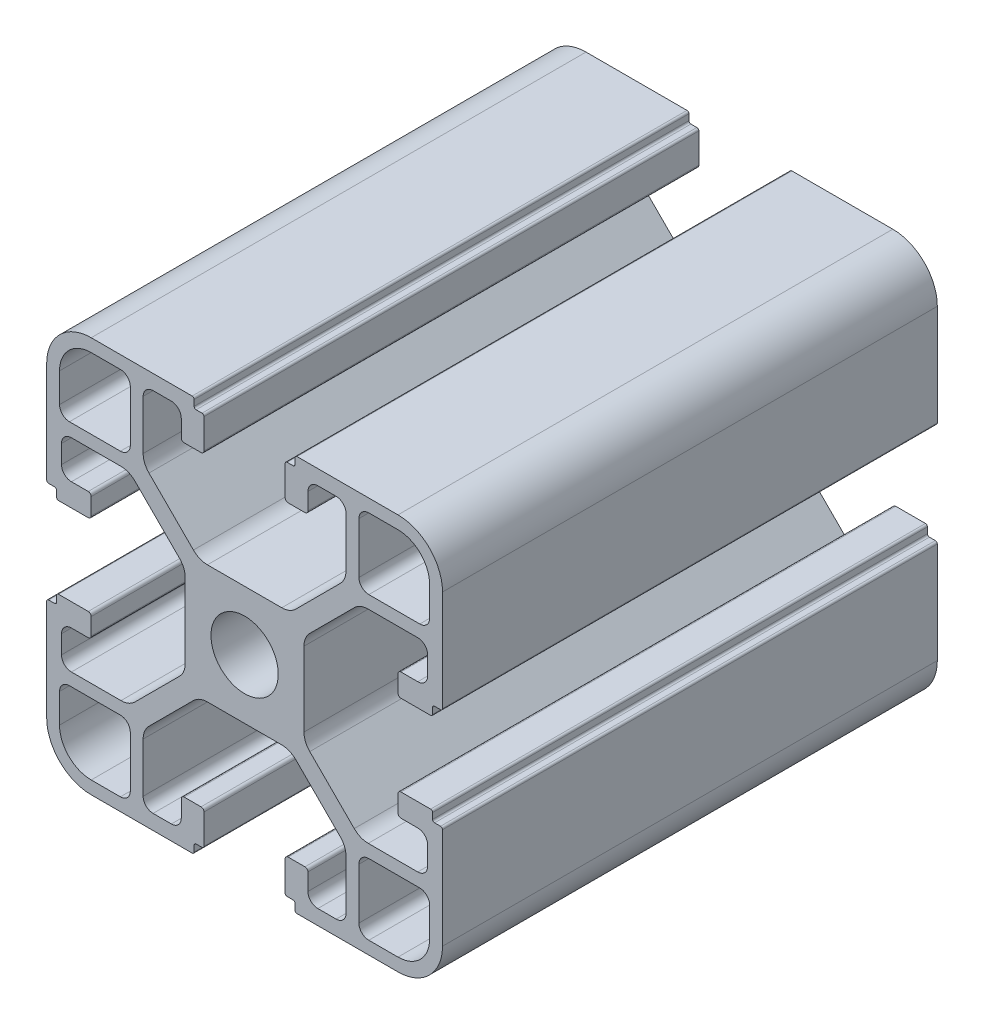
SolidWorks part; units mm, degrees
material "6063-T5"
ref_plane "Front Plane" through (0, 0, 0) normal (0, 0, 1) x (1, 0, 0)
ref_plane "Top Plane" through (0, 0, 0) normal (0, 1, 0) x (1, 0, 0)
ref_plane "Right Plane" through (0, 0, 0) normal (1, 0, 0) x (0, 0, -1)
sketch "Sketch2" plane through (0, 0, 0) normal (0, 0, 1) x (1, 0, 0)
  line L0 (4.5, 0) -> (14.7, 0)
  line L1 (40, 4.5) -> (40, 14.7)
  line L2 (35.5, 40) -> (25.3, 40)
  line L3 (0, 35.5) -> (0, 25.3)
  line L4 (15.9, 1.2) -> (15.9, 4.2)
  line L5 (24.1, 1.2) -> (24.1, 4.2)
  line L6 (38.8, 24.1) -> (35.8, 24.1)
  line L7 (35.5, 24.4) -> (35.5, 26.1)
  line L8 (14, 23.7574) -> (14, 16.2426)
  line L9 (16.2426, 14) -> (23.7574, 14)
  line L10 (26, 16.2426) -> (26, 23.7574)
  line L11 (13.4142, 14.8284) -> (8.9216, 10.3358)
  line L12 (23.7574, 26) -> (16.2426, 26)
  line L13 (4.5, 24.4) -> (4.5, 26.1)
  line L14 (1.2, 24.1) -> (4.2, 24.1)
  line L15 (15.9, 38.8) -> (15.9, 35.8)
  line L16 (14.8284, 26.5858) -> (10.3358, 31.0784)
  line L17 (13.4142, 25.1716) -> (8.9216, 29.6642)
  line L18 (14.8284, 13.4142) -> (10.3358, 8.9216)
  line L19 (25.1716, 13.4142) -> (29.6642, 8.9216)
  line L20 (26.5858, 14.8284) -> (31.0784, 10.3358)
  line L21 (26.5858, 25.1716) -> (31.0784, 29.6642)
  line L22 (25.1716, 26.5858) -> (29.6642, 31.0784)
  line L23 (24.1, 38.8) -> (24.1, 35.8)
  line L24 (14.7, 40) -> (4.5, 40)
  line L25 (25.3, 0) -> (35.5, 0)
  line L26 (38.8, 15.9) -> (35.8, 15.9)
  line L27 (40, 25.3) -> (40, 35.5)
  line L28 (1.2, 15.9) -> (4.2, 15.9)
  line L29 (0, 14.7) -> (0, 4.5)
  line L30 (4.5, 15.6) -> (4.5, 13.9)
  line L31 (35.5, 15.6) -> (35.5, 13.9)
  line L32 (15.6, 35.5) -> (13.9, 35.5)
  line L33 (24.4, 35.5) -> (26.1, 35.5)
  line L34 (15.6, 4.5) -> (13.9, 4.5)
  line L35 (24.4, 4.5) -> (26.1, 4.5)
  line L36 (12.6, 38.5) -> (10.75, 38.5)
  line L37 (1.5, 12.6) -> (1.5, 10.75)
  line L38 (27.4, 1.5) -> (29.25, 1.5)
  line L39 (38.5, 27.4) -> (38.5, 29.25)
  line L40 (38.5, 10.75) -> (38.5, 12.6)
  line L41 (29.25, 38.5) -> (27.4, 38.5)
  line L42 (1.5, 29.25) -> (1.5, 27.4)
  line L43 (10.75, 1.5) -> (12.6, 1.5)
  line L44 (35.8, 26.4) -> (37.5, 26.4)
  line L45 (35.8, 13.6) -> (37.5, 13.6)
  line L46 (4.2, 26.4) -> (2.5, 26.4)
  line L47 (13.6, 35.8) -> (13.6, 37.5)
  line L48 (26.4, 35.8) -> (26.4, 37.5)
  line L49 (4.2, 13.6) -> (2.5, 13.6)
  line L50 (13.6, 4.2) -> (13.6, 2.5)
  line L51 (26.4, 4.2) -> (26.4, 2.5)
  line L52 (9.75, 7.5074) -> (9.75, 2.5)
  line L53 (30.25, 7.5074) -> (30.25, 2.5)
  line L54 (9.75, 37.5) -> (9.75, 32.4926)
  line L55 (30.25, 37.5) -> (30.25, 32.4926)
  line L56 (32.4926, 30.25) -> (37.5, 30.25)
  line L57 (37.5, 9.75) -> (32.4926, 9.75)
  line L58 (2.5, 30.25) -> (7.5074, 30.25)
  line L59 (2.5, 9.75) -> (7.5074, 9.75)
  line L60 (31.55, 37.7) -> (31.55, 32.55)
  line L61 (32.55, 31.55) -> (37.7, 31.55)
  line L62 (1.3, 35.5) -> (1.3, 32.55)
  line L63 (4.5, 38.7) -> (7.45, 38.7)
  line L64 (32.55, 38.7) -> (35.5, 38.7)
  line L65 (38.7, 35.5) -> (38.7, 32.55)
  line L66 (8.45, 37.7) -> (8.45, 32.55)
  line L67 (2.3, 31.55) -> (7.45, 31.55)
  line L68 (1.3, 7.45) -> (1.3, 4.5)
  line L69 (2.3, 8.45) -> (7.45, 8.45)
  line L70 (8.45, 7.45) -> (8.45, 2.3)
  line L71 (4.5, 1.3) -> (7.45, 1.3)
  line L72 (31.55, 7.45) -> (31.55, 2.3)
  line L73 (32.55, 8.45) -> (37.7, 8.45)
  line L74 (38.7, 7.45) -> (38.7, 4.5)
  line L75 (32.55, 1.3) -> (35.5, 1.3)
  line L77 (14.9, 39.8) -> (14.9, 39.2)
  line L78 (15.1, 39) -> (15.7, 39)
  line L79 (25.1, 39.8) -> (25.1, 39.2)
  line L80 (24.9, 39) -> (24.3, 39)
  line L81 (25.1, 0.2) -> (25.1, 0.8)
  line L82 (24.9, 1) -> (24.3, 1)
  line L83 (14.9, 0.2) -> (14.9, 0.8)
  line L84 (15.1, 1) -> (15.7, 1)
  line L85 (0.2, 25.1) -> (0.8, 25.1)
  line L86 (1, 24.9) -> (1, 24.3)
  line L87 (0.2, 14.9) -> (0.8, 14.9)
  line L88 (1, 15.1) -> (1, 15.7)
  line L89 (39.8, 25.1) -> (39.2, 25.1)
  line L90 (39, 24.9) -> (39, 24.3)
  line L91 (39, 15.7) -> (39, 15.1)
  line L92 (39.2, 14.9) -> (39.8, 14.9)
  circle A0 centre (20, 20) radius 3.4
  arc A1 (1.3, 35.5) -> (4.5, 38.7) centre (4.5, 35.5) cw
  arc A2 (1.3, 4.5) -> (4.5, 1.3) centre (4.5, 4.5) ccw
  arc A3 (38.7, 4.5) -> (35.5, 1.3) centre (35.5, 4.5) cw
  arc A4 (35.5, 38.7) -> (38.7, 35.5) centre (35.5, 35.5) cw
  arc A5 (40, 35.5) -> (35.5, 40) centre (35.5, 35.5) ccw
  arc A6 (35.5, 0) -> (40, 4.5) centre (35.5, 4.5) ccw
  arc A7 (4.5, 0) -> (0, 4.5) centre (4.5, 4.5) cw
  arc A8 (4.5, 40) -> (0, 35.5) centre (4.5, 35.5) ccw
  arc A9 (13.4142, 14.8284) -> (14, 16.2426) centre (12, 16.2426) ccw
  arc A10 (7.5074, 9.75) -> (8.9216, 10.3358) centre (7.5074, 11.75) ccw
  arc A11 (9.75, 7.5074) -> (10.3358, 8.9216) centre (11.75, 7.5074) cw
  arc A12 (30.25, 7.5074) -> (29.6642, 8.9216) centre (28.25, 7.5074) ccw
  arc A13 (14.8284, 13.4142) -> (16.2426, 14) centre (16.2426, 12) cw
  arc A14 (25.1716, 13.4142) -> (23.7574, 14) centre (23.7574, 12) ccw
  arc A15 (32.4926, 9.75) -> (31.0784, 10.3358) centre (32.4926, 11.75) cw
  arc A16 (26.5858, 14.8284) -> (26, 16.2426) centre (28, 16.2426) cw
  arc A17 (32.4926, 30.25) -> (31.0784, 29.6642) centre (32.4926, 28.25) ccw
  arc A18 (26.5858, 25.1716) -> (26, 23.7574) centre (28, 23.7574) ccw
  arc A19 (13.4142, 25.1716) -> (14, 23.7574) centre (12, 23.7574) cw
  arc A20 (7.5074, 30.25) -> (8.9216, 29.6642) centre (7.5074, 28.25) cw
  arc A21 (9.75, 32.4926) -> (10.3358, 31.0784) centre (11.75, 32.4926) ccw
  arc A22 (30.25, 32.4926) -> (29.6642, 31.0784) centre (28.25, 32.4926) cw
  arc A23 (25.1716, 26.5858) -> (23.7574, 26) centre (23.7574, 28) cw
  arc A24 (14.8284, 26.5858) -> (16.2426, 26) centre (16.2426, 28) ccw
  arc A25 (37.7, 8.45) -> (38.7, 7.45) centre (37.7, 7.45) cw
  arc A26 (31.55, 2.3) -> (32.55, 1.3) centre (32.55, 2.3) ccw
  arc A27 (31.55, 7.45) -> (32.55, 8.45) centre (32.55, 7.45) cw
  arc A28 (8.45, 2.3) -> (7.45, 1.3) centre (7.45, 2.3) cw
  arc A29 (1.3, 7.45) -> (2.3, 8.45) centre (2.3, 7.45) cw
  arc A30 (7.45, 8.45) -> (8.45, 7.45) centre (7.45, 7.45) cw
  arc A31 (38.7, 32.55) -> (37.7, 31.55) centre (37.7, 32.55) cw
  arc A32 (31.55, 32.55) -> (32.55, 31.55) centre (32.55, 32.55) ccw
  arc A33 (31.55, 37.7) -> (32.55, 38.7) centre (32.55, 37.7) cw
  arc A34 (7.45, 38.7) -> (8.45, 37.7) centre (7.45, 37.7) cw
  arc A35 (8.45, 32.55) -> (7.45, 31.55) centre (7.45, 32.55) cw
  arc A36 (1.3, 32.55) -> (2.3, 31.55) centre (2.3, 32.55) ccw
  arc A37 (30.25, 2.5) -> (29.25, 1.5) centre (29.25, 2.5) cw
  arc A38 (26.4, 2.5) -> (27.4, 1.5) centre (27.4, 2.5) ccw
  arc A39 (13.6, 2.5) -> (12.6, 1.5) centre (12.6, 2.5) cw
  arc A40 (9.75, 2.5) -> (10.75, 1.5) centre (10.75, 2.5) ccw
  arc A41 (26.4, 37.5) -> (27.4, 38.5) centre (27.4, 37.5) cw
  arc A42 (30.25, 37.5) -> (29.25, 38.5) centre (29.25, 37.5) ccw
  arc A43 (37.5, 26.4) -> (38.5, 27.4) centre (37.5, 27.4) ccw
  arc A44 (37.5, 30.25) -> (38.5, 29.25) centre (37.5, 29.25) cw
  arc A45 (37.5, 13.6) -> (38.5, 12.6) centre (37.5, 12.6) cw
  arc A46 (37.5, 9.75) -> (38.5, 10.75) centre (37.5, 10.75) ccw
  arc A47 (2.5, 9.75) -> (1.5, 10.75) centre (2.5, 10.75) cw
  arc A48 (2.5, 13.6) -> (1.5, 12.6) centre (2.5, 12.6) ccw
  arc A49 (2.5, 26.4) -> (1.5, 27.4) centre (2.5, 27.4) cw
  arc A50 (2.5, 30.25) -> (1.5, 29.25) centre (2.5, 29.25) ccw
  arc A51 (9.75, 37.5) -> (10.75, 38.5) centre (10.75, 37.5) cw
  arc A52 (13.6, 37.5) -> (12.6, 38.5) centre (12.6, 37.5) ccw
  arc A53 (26.1, 35.5) -> (26.4, 35.8) centre (26.1, 35.8) ccw
  arc A54 (24.1, 35.8) -> (24.4, 35.5) centre (24.4, 35.8) ccw
  arc A55 (15.9, 35.8) -> (15.6, 35.5) centre (15.6, 35.8) cw
  arc A56 (13.9, 35.5) -> (13.6, 35.8) centre (13.9, 35.8) cw
  arc A57 (13.9, 4.5) -> (13.6, 4.2) centre (13.9, 4.2) ccw
  arc A58 (15.9, 4.2) -> (15.6, 4.5) centre (15.6, 4.2) ccw
  arc A59 (24.1, 4.2) -> (24.4, 4.5) centre (24.4, 4.2) cw
  arc A60 (26.1, 4.5) -> (26.4, 4.2) centre (26.1, 4.2) cw
  arc A61 (35.5, 13.9) -> (35.8, 13.6) centre (35.8, 13.9) ccw
  arc A62 (35.8, 15.9) -> (35.5, 15.6) centre (35.8, 15.6) ccw
  arc A63 (35.8, 24.1) -> (35.5, 24.4) centre (35.8, 24.4) cw
  arc A64 (35.5, 26.1) -> (35.8, 26.4) centre (35.8, 26.1) cw
  arc A65 (4.5, 13.9) -> (4.2, 13.6) centre (4.2, 13.9) cw
  arc A66 (4.2, 15.9) -> (4.5, 15.6) centre (4.2, 15.6) cw
  arc A67 (4.2, 24.1) -> (4.5, 24.4) centre (4.2, 24.4) ccw
  arc A68 (4.5, 26.1) -> (4.2, 26.4) centre (4.2, 26.1) ccw
  arc A69 (25.3, 0) -> (25.1, 0.2) centre (25.3, 0.2) cw
  arc A70 (25.1, 0.8) -> (24.9, 1) centre (24.9, 0.8) ccw
  arc A71 (24.3, 1) -> (24.1, 1.2) centre (24.3, 1.2) cw
  arc A72 (14.7, 0) -> (14.9, 0.2) centre (14.7, 0.2) ccw
  arc A73 (14.9, 0.8) -> (15.1, 1) centre (15.1, 0.8) cw
  arc A74 (15.7, 1) -> (15.9, 1.2) centre (15.7, 1.2) ccw
  arc A75 (39.8, 14.9) -> (40, 14.7) centre (39.8, 14.7) cw
  arc A76 (39, 15.1) -> (39.2, 14.9) centre (39.2, 15.1) ccw
  arc A77 (38.8, 15.9) -> (39, 15.7) centre (38.8, 15.7) cw
  arc A78 (0, 25.3) -> (0.2, 25.1) centre (0.2, 25.3) ccw
  arc A79 (0.8, 25.1) -> (1, 24.9) centre (0.8, 24.9) cw
  arc A80 (1, 24.3) -> (1.2, 24.1) centre (1.2, 24.3) ccw
  arc A81 (0, 14.7) -> (0.2, 14.9) centre (0.2, 14.7) cw
  arc A82 (0.8, 14.9) -> (1, 15.1) centre (0.8, 15.1) ccw
  arc A83 (1, 15.7) -> (1.2, 15.9) centre (1.2, 15.7) cw
  arc A84 (39, 24.3) -> (38.8, 24.1) centre (38.8, 24.3) cw
  arc A85 (39.2, 25.1) -> (39, 24.9) centre (39.2, 24.9) ccw
  arc A86 (40, 25.3) -> (39.8, 25.1) centre (39.8, 25.3) cw
  arc A87 (24.3, 39) -> (24.1, 38.8) centre (24.3, 38.8) ccw
  arc A88 (25.1, 39.2) -> (24.9, 39) centre (24.9, 39.2) cw
  arc A89 (25.3, 40) -> (25.1, 39.8) centre (25.3, 39.8) ccw
  arc A90 (14.9, 39.2) -> (15.1, 39) centre (15.1, 39.2) ccw
  arc A91 (15.7, 39) -> (15.9, 38.8) centre (15.7, 38.8) cw
  arc A92 (14.7, 40) -> (14.9, 39.8) centre (14.7, 39.8) cw
  point P93 (0, 0)
extrude "Boss-Extrude1" add sketch "Sketch2" along normal blind 50
